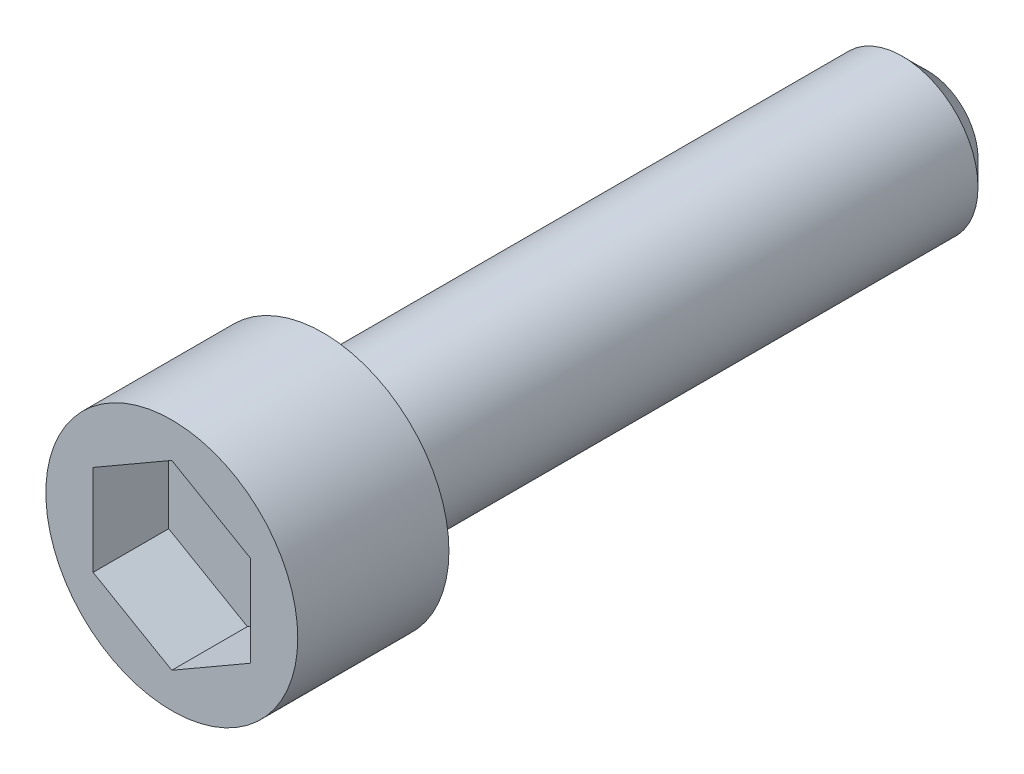
SolidWorks part; units mm, degrees
ref_plane "前视基准面" through (0, 0, 0) normal (0, 0, 1) x (1, 0, 0)
ref_plane "上视基准面" through (0, 0, 0) normal (0, 1, 0) x (1, 0, 0)
ref_plane "右视基准面" through (0, 0, 0) normal (1, 0, 0) x (0, 0, -1)
sketch "草图1" plane through (0, 0, 0) normal (0, 0, 1) x (1, 0, 0)
  circle A0 centre (0, 0) radius 1.5
extrude "凸台-拉伸1" add sketch "草图1" along normal blind 12
sketch "草图2" plane through (0, 0, 12) normal (0, 0, 1) x (1, 0, 0)
  circle A0 centre (0, 0) radius 2.5
extrude "凸台-拉伸2" add sketch "草图2" along normal blind 3
sketch "草图3" plane through (0, 0, 15) normal (0, 0, 1) x (1, 0, 0)
  line L1 (0, 1.8034) -> (-1.5618, 0.9017)
  line L2 (-1.5618, 0.9017) -> (-1.5618, -0.9017)
  line L3 (-1.5618, -0.9017) -> (0, -1.8034)
  line L4 (0, -1.8034) -> (1.5618, -0.9017)
  line L5 (1.5618, -0.9017) -> (1.5618, 0.9017)
  line L6 (1.5618, 0.9017) -> (0, 1.8034)
  circle A0 centre (0, 0) radius 1.5618 construction
extrude "切除-拉伸1" cut sketch "草图3" against normal blind 1.5
chamfer "倒角1" distance 0.5 angle 45 1 edges at (1.5, 0, 0)
